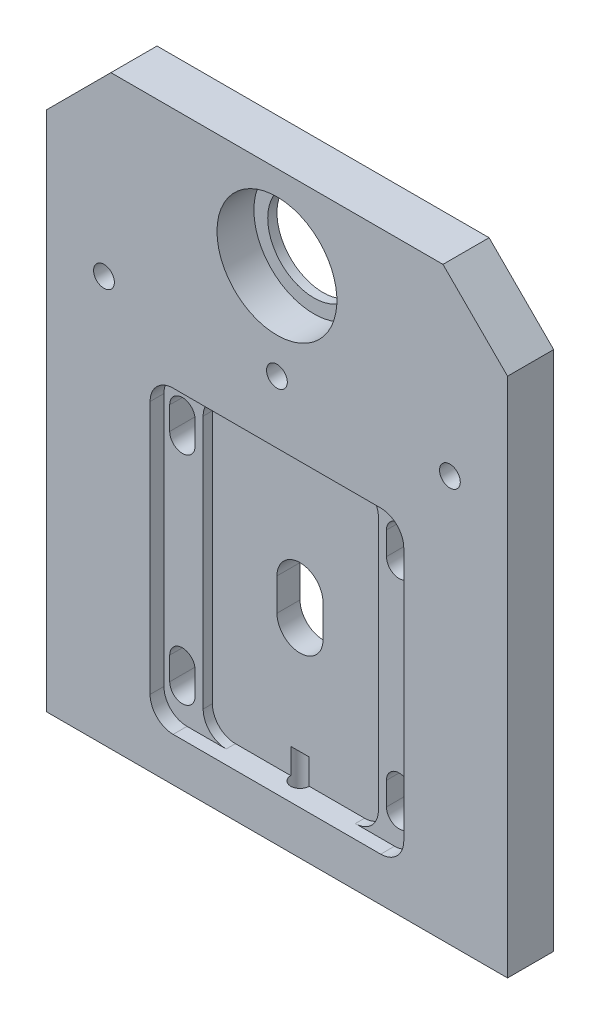
SolidWorks part; units mm, degrees
ref_plane "Piano frontale" through (0, 0, 0) normal (0, 0, 1) x (1, 0, 0)
ref_plane "Piano superiore" through (0, 0, 0) normal (0, 1, 0) x (1, 0, 0)
ref_plane "Piano destro" through (0, 0, 0) normal (1, 0, 0) x (0, 0, -1)
sketch "Schizzo1" plane through (0, 0, 0) normal (0, 0, 1) x (1, 0, 0)
  line L0 (0, 113) -> (14, 127)
  line L1 (0, 0) -> (100, 0)
  line L2 (0, 0) -> (0, 113)
  line L3 (14, 127) -> (86, 127)
  line L4 (100, 0) -> (100, 113)
  line L5 (86, 127) -> (100, 113)
  point P1 (100, 127)
  point P2 (0, 127)
  dimension "D1" = 127
  dimension "D2" = 100
extrude "Estrusione-Estrusione1" add sketch "Schizzo1" against normal blind 10
sketch "Schizzo2" plane through (0, 0, 0) normal (0, 0, 1) x (1, 0, 0)
  line L0 (86, 127) -> (14, 127) construction
  line L2 (50, 0) -> (50, 127) construction
  line L3 (0, 0) -> (100, 0) construction
  circle A0 centre (50, 108.7) radius 10
  dimension "D2" = 20
  dimension "D1" = 18.3
extrude "Taglio-Estrusione1" cut sketch "Schizzo2" against normal blind 10
sketch "Schizzo3" plane through (0, 0, 0) normal (0, 0, 1) x (1, 0, 0)
  line L0 (86, 127) -> (14, 127) construction
  line L1 (95, 88) -> (0, 88) construction
  line L2 (0, 0) -> (100, 0) construction
  line L3 (0, 113) -> (0, 0) construction
  line L6 (50, 0) -> (50, 127) construction
  circle A0 centre (12.5, 88) radius 2.25
  circle A1 centre (50, 88) radius 2.25
  circle A2 centre (87.5, 88) radius 2.25
  dimension "D5" = 4.5
  dimension "D1" = 37.5
  dimension "D2" = 88
extrude "Taglio-Estrusione2" cut sketch "Schizzo3" against normal blind 10
sketch "Schizzo4" plane through (0, 0, 0) normal (0, 0, 1) x (1, 0, 0)
  line L0 (50, 0) -> (50, 127) construction
  line L1 (0, 0) -> (100, 0) construction
  line L2 (0, 88.7572) -> (0, -18.8818) construction
  line L3 (0, 113) -> (0, 0) construction
  line L4 (86, 127) -> (14, 127) construction
  line L8 (27.5, 74.5) -> (72.5, 74.5)
  line L9 (22.5, 69.5) -> (22.5, 14.5)
  line L10 (27.5, 9.5) -> (72.5, 9.5)
  line L11 (77.5, 69.5) -> (77.5, 14.5)
  arc A0 (22.5, 14.5) -> (27.5, 9.5) centre (27.5, 14.5) ccw
  arc A1 (72.5, 9.5) -> (77.5, 14.5) centre (72.5, 14.5) ccw
  arc A2 (77.5, 69.5) -> (72.5, 74.5) centre (72.5, 69.5) ccw
  arc A3 (27.5, 74.5) -> (22.5, 69.5) centre (27.5, 69.5) ccw
  point P23 (77.5, 9.5)
  point P28 (22.5, 74.5)
  dimension "D5" = 5
  dimension "D1" = 45
extrude "Taglio-Estrusione3" cut sketch "Schizzo4" against normal blind 3
sketch "Schizzo5" plane through (0, 0, -3) normal (0, 0, 1) x (1, 0, 0)
  line L0 (0, 0) -> (0, -14.3774) construction
  line L1 (50, 0) -> (50, 127) construction
  line L2 (0, 0) -> (100, 0) construction
  line L3 (86, 127) -> (14, 127) construction
  line L7 (27.5, 9.5) -> (72.5, 9.5) construction
  line L8 (36, 74.5) -> (64, 74.5)
  line L9 (31, 69.5) -> (31, 14.5)
  line L10 (36, 9.5) -> (64, 9.5)
  line L11 (69, 69.5) -> (69, 14.5)
  arc A0 (31, 14.5) -> (36, 9.5) centre (36, 14.5) ccw
  arc A1 (64, 9.5) -> (69, 14.5) centre (64, 14.5) ccw
  arc A2 (64, 74.5) -> (69, 69.5) centre (64, 69.5) cw
  arc A3 (36, 74.5) -> (31, 69.5) centre (36, 69.5) ccw
  point P21 (69, 9.5)
  dimension "D3" = 5
  dimension "D1" = 38
  dimension "D2" = 65
extrude "Taglio-Estrusione4" cut sketch "Schizzo5" against normal blind 2
sketch "Schizzo6" plane through (0, 0, -5) normal (0, 0, 1) x (1, 0, 0)
  line L0 (31, 42) -> (69, 42) construction
  line L1 (31, 69.5) -> (31, 14.5) construction
  line L2 (69, 14.5) -> (69, 69.5) construction
  line L3 (50, 74.5) -> (50, 9.5) construction
  line L4 (64, 74.5) -> (36, 74.5) construction
  line L5 (36, 9.5) -> (64, 9.5) construction
  line L6 (50, 45.5) -> (50, 38.5) construction
  line L13 (54.9932, 45.5) -> (54.9932, 38.5)
  line L14 (45.0068, 45.5) -> (45.0068, 38.5)
  arc A0 (54.9932, 45.5) -> (45.0068, 45.5) centre (50, 45.5) ccw
  arc A1 (45.0068, 38.5) -> (54.9932, 38.5) centre (50, 38.5) ccw
  point P12 (50, 42)
  point P19 (50, 42)
  dimension "D3" = 29
  dimension "D1" = 4.9932
  dimension "D2" = 7
  dimension "D4" = 4.9932
extrude "Taglio-Estrusione5" cut sketch "Schizzo6" against normal through all
sketch "Schizzo7" plane through (0, 0, -3) normal (0, 0, 1) x (1, 0, 0)
  line L0 (22.5, 42) -> (31, 42) construction
  line L1 (22.5, 69.5) -> (22.5, 14.5) construction
  line L2 (31, 69.5) -> (31, 14.5) construction
  line L3 (26.5, 63) -> (26.5, 68) construction
  line L4 (31, 42) -> (69, 42) construction
  line L5 (26.5, 65.5) -> (73.5, 65.5) construction
  line L6 (26.5, 65.5) -> (26.5, 18.5) construction
  line L7 (26.5, 18.5) -> (73.5, 18.5) construction
  line L8 (73.5, 65.5) -> (73.5, 18.5) construction
  line L9 (26.5, 65.5) -> (73.5, 18.5) construction
  line L10 (26.5, 18.5) -> (73.5, 65.5) construction
  line L11 (69, 14.5) -> (69, 69.5) construction
  line L12 (50, 42) -> (50, 0) construction
  line L13 (23.75, 63) -> (23.75, 68)
  line L14 (29.25, 63) -> (29.25, 68)
  line L15 (73.5, 63) -> (73.5, 68) construction
  line L16 (70.75, 63) -> (70.75, 68)
  line L17 (76.25, 63) -> (76.25, 68)
  line L18 (26.5, 16) -> (26.5, 21) construction
  line L19 (23.75, 16) -> (23.75, 21)
  line L20 (29.25, 16) -> (29.25, 21)
  line L21 (73.5, 16) -> (73.5, 21) construction
  line L22 (70.75, 16) -> (70.75, 21)
  line L23 (76.25, 16) -> (76.25, 21)
  line L24 (0, 0) -> (100, 0) construction
  arc A0 (23.75, 63) -> (29.25, 63) centre (26.5, 63) ccw
  arc A1 (29.25, 68) -> (23.75, 68) centre (26.5, 68) ccw
  arc A2 (70.75, 63) -> (76.25, 63) centre (73.5, 63) ccw
  arc A3 (76.25, 68) -> (70.75, 68) centre (73.5, 68) ccw
  arc A4 (23.75, 16) -> (29.25, 16) centre (26.5, 16) ccw
  arc A5 (29.25, 21) -> (23.75, 21) centre (26.5, 21) ccw
  arc A6 (70.75, 16) -> (76.25, 16) centre (73.5, 16) ccw
  arc A7 (76.25, 21) -> (70.75, 21) centre (73.5, 21) ccw
  point P8 (50, 42)
  point P18 (26.5, 65.5)
  point P25 (73.5, 65.5)
  point P31 (26.5, 18.5)
  point P38 (73.5, 18.5)
  dimension "D1" = 47
  dimension "D2" = 47
extrude "Taglio-Estrusione6" cut sketch "Schizzo7" against normal through all
sketch "Schizzo8" plane through (0, 0, 0) normal (0, 0, -1) x (-1, 0, 0)
  circle A0 centre (-50, 108.7) radius 13
  dimension "D1" = 26
extrude "Taglio-Estrusione7" cut sketch "Schizzo8" along normal blind 8
sketch "Schizzo9" plane through (0, 0, -10) normal (0, 0, -1) x (-1, 0, 0)
  circle A0 centre (-85, 83) radius 4
  circle A1 centre (-50, 88) radius 4
  circle A2 centre (-12.5, 88) radius 4
  dimension "D1" = 8
  dimension "D2" = 8
  dimension "D3" = 8
extrude "Taglio-Estrusione8" cut sketch "Schizzo9" against normal blind 4
sketch "Schizzo10" plane through (0, 0, 0) normal (0, -1, 0) x (1, 0, 0)
  line L0 (50, 0) -> (50, -10) construction
  line L4 (0, 0) -> (100, 0) construction
  line L9 (0, -10) -> (100, -10) construction
  line L10 (100, -5) -> (0, -5) construction
  line L11 (100, -10) -> (100, 0) construction
  circle A0 centre (50, -5) radius 2
  circle A1 centre (19.5, -5) radius 2
  circle A2 centre (80.5, -5) radius 2
  dimension "D1" = 4
  dimension "D2" = 4
  dimension "D3" = 30.5
extrude "Taglio-Estrusione9" cut sketch "Schizzo10" against normal blind 15
